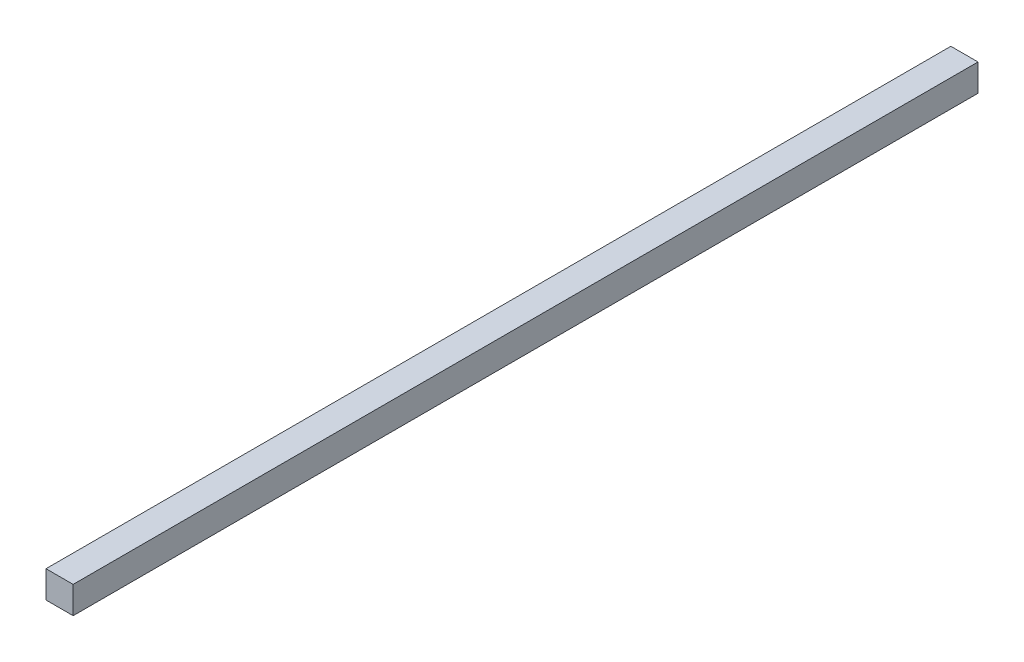
SolidWorks part; units mm, degrees
ref_plane "前视基准面" through (0, 0, 0) normal (0, 0, 1) x (1, 0, 0)
ref_plane "上视基准面" through (0, 0, 0) normal (0, 1, 0) x (1, 0, 0)
ref_plane "右视基准面" through (0, 0, 0) normal (1, 0, 0) x (0, 0, -1)
sketch "草图1" plane through (0, 0, 0) normal (0, 0, 1) x (1, 0, 0)
  line L1 (-15, -15) -> (15, -15)
  line L2 (-15, -15) -> (-15, 15)
  line L3 (-15, 15) -> (15, 15)
  line L4 (15, -15) -> (15, 15)
  line L5 (-15, -15) -> (15, 15) construction
  line L6 (-15, 15) -> (15, -15) construction
  point P0 (0, 0)
  dimension "D1" = 30
extrude "凸台-拉伸1" add sketch "草图1" along normal blind 1000
